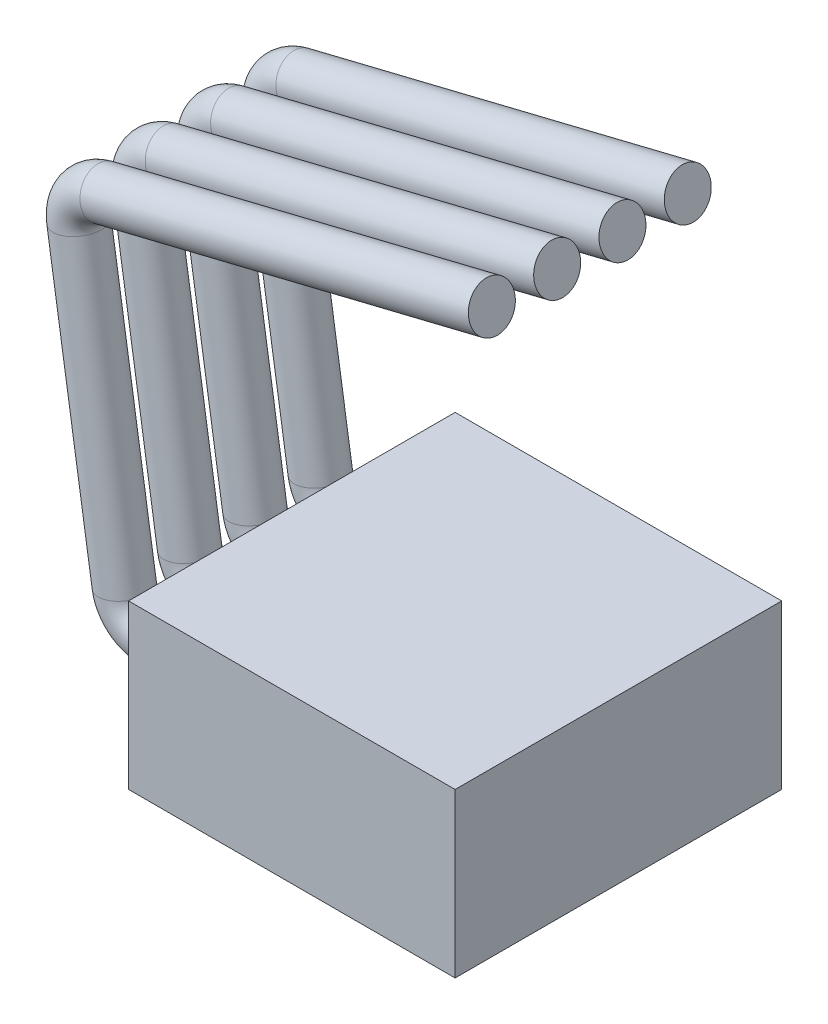
SolidWorks part; units mm, degrees
ref_plane "Спереди" through (0, 0, 0) normal (0, 0, 1) x (1, 0, 0)
ref_plane "Сверху" through (0, 0, 0) normal (0, 1, 0) x (1, 0, 0)
ref_plane "Справа" through (0, 0, 0) normal (1, 0, 0) x (0, 0, -1)
sketch "Эскиз1" plane through (0, 0, 0) normal (0, 1, 0) x (1, 0, 0)
  line L1 (-2.7318, 1.2193) -> (2.2682, 1.2193)
  line L2 (-2.7318, 1.2193) -> (-2.7318, -3.7807)
  line L3 (-2.7318, -3.7807) -> (2.2682, -3.7807)
  line L4 (2.2682, 1.2193) -> (2.2682, -3.7807)
  dimension "D1" = 5
  dimension "D2" = 5
extrude "Бобышка-Вытянуть1" add sketch "Эскиз1" along normal blind 2.5
sketch "Эскиз2" plane through (-2.7318, 0, 0) normal (-1, 0, 0) x (0, 0, 1)
  line L0 (-0.2193, 1.6) -> (-0.2193, 0.9) construction
  line L1 (0.7807, 1.6) -> (0.7807, 0.9) construction
  line L2 (-0.5693, 1.25) -> (0.1307, 1.25) construction
  line L3 (0.4307, 1.25) -> (1.1307, 1.25) construction
  line L4 (1.7807, 1.6) -> (1.7807, 0.9) construction
  line L5 (1.4307, 1.25) -> (2.1307, 1.25) construction
  line L6 (2.7807, 1.6) -> (2.7807, 0.9) construction
  line L7 (-1.2193, 2.5) -> (-1.2193, 0) construction
  line L8 (-1.2193, 2.5) -> (3.7807, 2.5) construction
  line L11 (3.7807, 2.5) -> (3.7807, 0) construction
  circle A0 centre (-0.2193, 1.25) radius 0.35
  circle A3 centre (0.7807, 1.25) radius 0.35
  circle A4 centre (1.7807, 1.25) radius 0.35
  circle A5 centre (2.7807, 1.25) radius 0.35
  dimension "D1" = 0.7
  dimension "D2" = 0.7
  dimension "D3" = 0.7
  dimension "D4" = 0.7
  dimension "D6" = 1.25
  dimension "D7" = 1.25
  dimension "D8" = 1
  dimension "D9" = 1
  dimension "D10" = 1
  dimension "D11" = 1
  dimension "D13" = 1
  dimension "D5" = 1.25
ref_plane "Плоскость6" through (0, 0, 2.7807) normal (0, 0, 1) x (1, 0, 0)
sketch "Эскиз9" plane through (0, 0, 2.7807) normal (0, 0, 1) x (1, 0, 0)
  line L0 (-2.7318, 1.25) -> (-3.3032, 1.25)
  line L1 (-4.1164, 6.7241) -> (1.8302, 8.1836)
  line L2 (-2.7318, 1.6) -> (-2.7318, 0.9) construction
  line L3 (-3.7973, 1.6736) -> (-4.4914, 6.1621)
  arc A0 (-3.3032, 1.25) -> (-3.7973, 1.6736) centre (-3.3032, 1.75) cw
  arc A1 (-4.4914, 6.1621) -> (-4.1164, 6.7241) centre (-3.9972, 6.2385) cw
  point P9 (-3.7318, 1.25)
  point P11 (-4.5614, 6.6149)
  dimension "D3" = 0.5
  dimension "D5" = 0.5
  dimension "D1" = 98.79
  dimension "D2" = 1
  dimension "D4" = 5
  dimension "D6" = 95
  dimension "D7" = 13.79
sweep "По траектории6" add profiles "Эскиз2" path "Эскиз9"
equation "\"D6@Эскиз2\"=\"D5@Эскиз2\""
equation "\"D7@Эскиз2\"=\"D5@Эскиз2\""
equation "\"D9@Эскиз2\"=\"D8@Эскиз2\""
equation "\"D11@Эскиз2\"=\"D8@Эскиз2\""
equation "\"D10@Эскиз2\"=\"D8@Эскиз2\""
